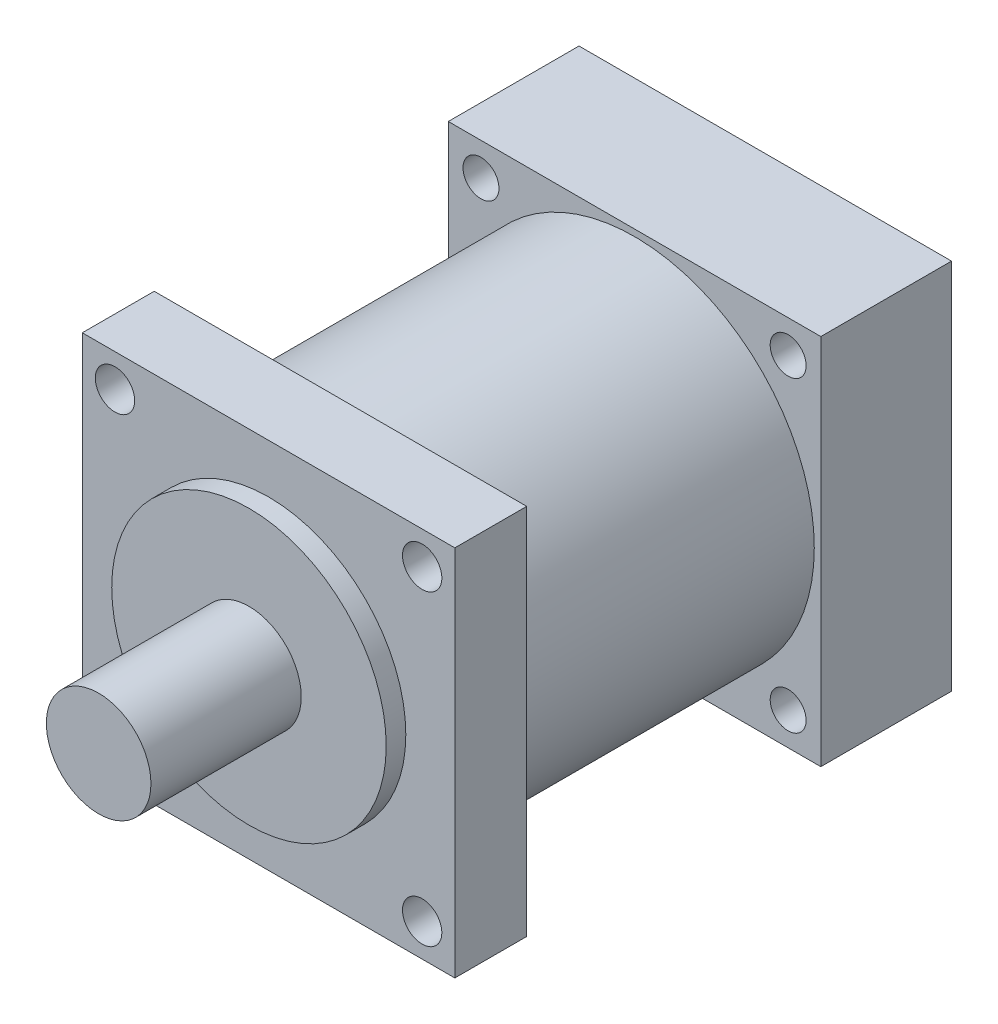
SolidWorks part; units mm, degrees
ref_plane "前视基准面" through (0, 0, 0) normal (0, 0, 1) x (1, 0, 0)
ref_plane "上视基准面" through (0, 0, 0) normal (0, 1, 0) x (1, 0, 0)
ref_plane "右视基准面" through (0, 0, 0) normal (1, 0, 0) x (0, 0, -1)
sketch "草图1" plane through (0, 0, 0) normal (0, 0, 1) x (1, 0, 0)
  line L0 (-23.5032, 11.7516) -> (33.4968, 11.7516) construction
  line L1 (-23.5032, 40.2516) -> (33.4968, 40.2516)
  line L2 (-23.5032, 40.2516) -> (-23.5032, -16.7484)
  line L3 (-23.5032, -16.7484) -> (33.4968, -16.7484)
  line L4 (33.4968, 40.2516) -> (33.4968, -16.7484)
  line L5 (4.9968, 40.2516) -> (4.9968, -16.7484) construction
  line L6 (-23.5032, 40.2516) -> (33.4968, -16.7484) construction
  circle A0 centre (-18.5032, 35.2516) radius 3.0101
  circle A1 centre (28.4968, 35.2516) radius 3.0101
  circle A2 centre (-18.5032, -11.7484) radius 3.0101
  circle A3 centre (28.4968, -11.7484) radius 3.0101
  point P10 (0, 0)
  point P12 (-17.5765, 34.3249)
  dimension "D3" = 23.5
  dimension "D1" = 57
  dimension "D2" = 57
extrude "凸台-拉伸1" add sketch "草图1" along normal blind 11
sketch "草图2" plane through (0, 0, 11) normal (0, 0, 1) x (1, 0, 0)
  line L0 (-23.5032, 40.2516) -> (33.4968, -16.7484) construction
  line L1 (33.4968, 40.2516) -> (-23.5032, -16.7484) construction
  circle A0 centre (4.9968, 11.7516) radius 21
  dimension "D1" = 42
extrude "凸台-拉伸2" add sketch "草图2" along normal blind 3
sketch "草图3" plane through (0, 0, 14) normal (0, 0, 1) x (1, 0, 0)
  line L0 (4.9968, 32.7516) -> (4.9968, -9.2484) construction
  circle A0 centre (4.9968, 11.7516) radius 21 construction
  circle A1 centre (4.9968, 11.7516) radius 21 construction
  circle A2 centre (4.9968, 11.7516) radius 8
  dimension "D1" = 16
extrude "凸台-拉伸3" add sketch "草图3" along normal blind 23
sketch "草图4" plane through (0, 0, 0) normal (0, 0, -1) x (-1, 0, 0)
  line L0 (-33.4968, 40.2516) -> (23.5032, -16.7484) construction
  line L1 (23.5032, 40.2516) -> (-33.4968, -16.7484) construction
  circle A0 centre (-4.9968, 11.7516) radius 27.5
  dimension "D1" = 55
extrude "凸台-拉伸4" add sketch "草图4" along normal blind 45
sketch "草图5" plane through (0, 0, -45) normal (0, 0, -1) x (-1, 0, 0)
  line L1 (-33.4968, -16.7484) -> (23.5032, -16.7484)
  line L2 (-33.4968, -16.7484) -> (-33.4968, 40.2516)
  line L3 (-33.4968, 40.2516) -> (23.5032, 40.2516)
  line L4 (23.5032, -16.7484) -> (23.5032, 40.2516)
  line L5 (-33.4968, -16.7484) -> (23.5032, 40.2516) construction
  line L6 (-33.4968, 40.2516) -> (23.5032, -16.7484) construction
  point P0 (-4.9968, 11.7516)
  dimension "D1" = 57
  dimension "D2" = 57
extrude "凸台-拉伸5" add sketch "草图5" along normal blind 20
sketch "草图6" plane through (0, 0, -65) normal (0, 0, -1) x (-1, 0, 0)
  line L0 (-33.4968, 40.2516) -> (23.5032, -16.7484) construction
  line L1 (23.5032, 40.2516) -> (-33.4968, -16.7484) construction
  line L2 (-4.9968, 40.2516) -> (-4.9968, -16.7484) construction
  line L3 (23.5032, 40.2516) -> (-33.4968, 40.2516) construction
  line L4 (-33.4968, -16.7484) -> (23.5032, -16.7484) construction
  circle A0 centre (-28.4968, 35.2516) radius 2.75
  circle A1 centre (18.5032, 35.2516) radius 2.75
  circle A2 centre (18.5032, -11.7484) radius 2.75
  circle A3 centre (-28.4968, -11.7484) radius 2.75
  dimension "D1" = 5.5
  dimension "D2" = 23.5
extrude "切除-拉伸1" cut sketch "草图6" against normal through all
sketch "草图7" plane through (0, 0, -65) normal (0, 0, -1) x (-1, 0, 0)
  line L0 (-33.4968, 40.2516) -> (23.5032, -16.7484) construction
  circle A0 centre (-4.9968, 11.7516) radius 22.0114
  point P2 (0, 0)
  point P3 (-4.9968, 11.7516)
extrude "切除-拉伸2" cut sketch "草图7" against normal blind 30
